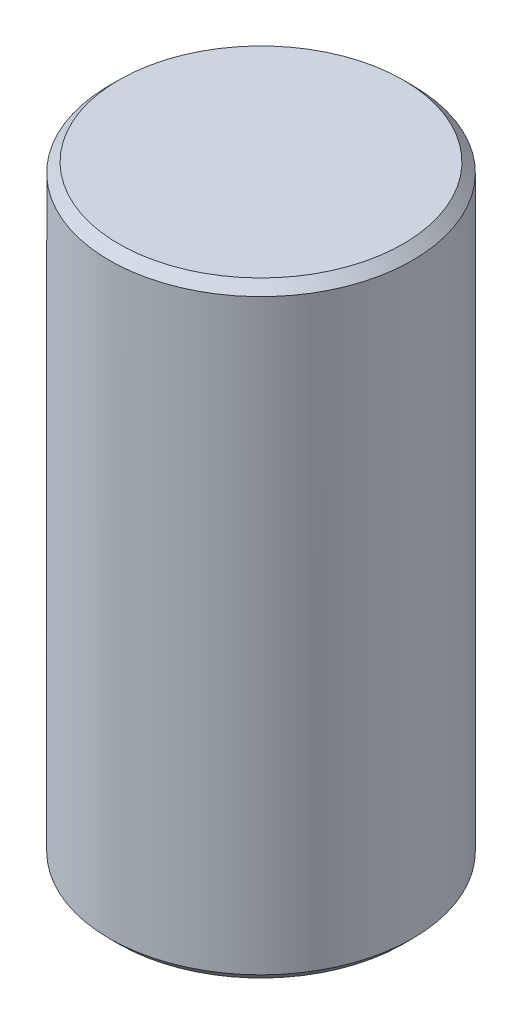
SolidWorks part; units mm, degrees
ref_plane "Front Plane" through (0, 0, 0) normal (0, 0, 1) x (1, 0, 0)
ref_plane "Top Plane" through (0, 0, 0) normal (0, 1, 0) x (1, 0, 0)
ref_plane "Right Plane" through (0, 0, 0) normal (1, 0, 0) x (0, 0, -1)
sketch "Sketch1" plane through (0, 0, 0) normal (0, 1, 0) x (1, 0, 0)
  circle A0 centre (0, 0) radius 6.35
  dimension "D1" = 12.7
extrude "Boss-Extrude1" add sketch "Sketch1" along normal blind 25.4
chamfer "Chamfer1" distance 0.3969 angle 45 2 edges at (0, 0, 6.35) (0, 25.4, 6.35)
